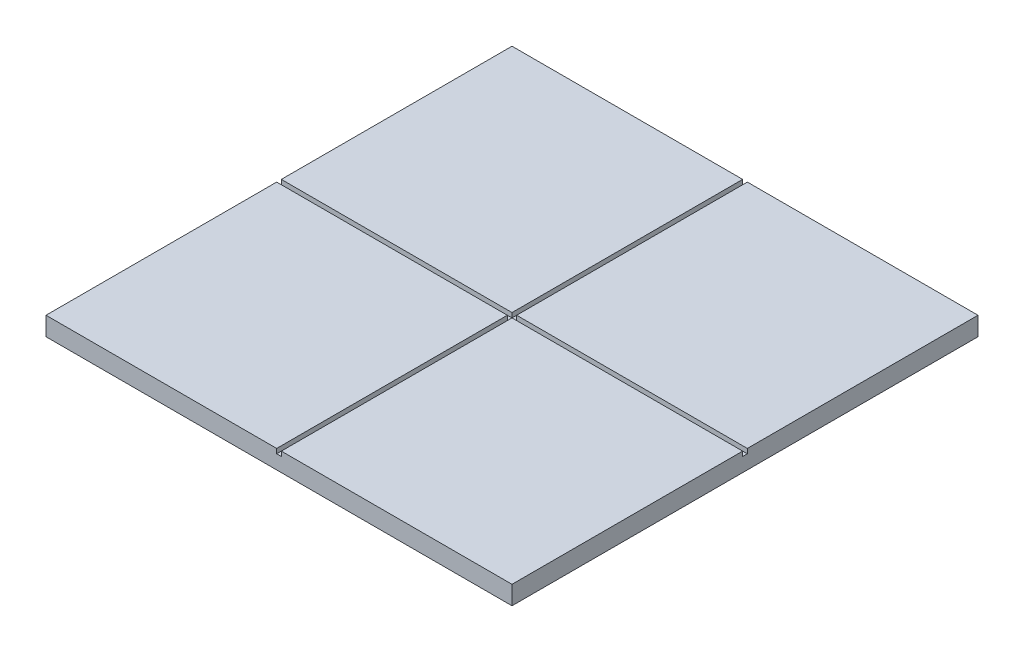
SolidWorks part; units mm, degrees
ref_plane "Front Plane" through (0, 0, 0) normal (0, 0, 1) x (1, 0, 0)
ref_plane "Top Plane" through (0, 0, 0) normal (0, 1, 0) x (1, 0, 0)
ref_plane "Right Plane" through (0, 0, 0) normal (1, 0, 0) x (0, 0, -1)
sketch "Sketch1" plane through (0, 0, 0) normal (0, 1, 0) x (1, 0, 0)
  line L1 (0, 0) -> (50, 0)
  line L2 (0, 0) -> (0, 50)
  line L3 (0, 50) -> (50, 50)
  line L4 (50, 0) -> (50, 50)
  dimension "D1" = 50
  dimension "D2" = 50
extrude "Boss-Extrude1" add sketch "Sketch1" along normal blind 2
sketch "Sketch2" plane through (0, 2, 0) normal (0, 1, 0) x (1, 0, 0)
  line L0 (50, 50) -> (0, 50) construction
  line L1 (24.75, 50) -> (25.25, 50)
  line L2 (24.75, 50) -> (24.75, 0)
  line L3 (24.75, 0) -> (25.25, 0)
  line L4 (25.25, 50) -> (25.25, 0)
  line L5 (0, 0) -> (50, 0) construction
  line L6 (0, 50) -> (0, 0) construction
  line L7 (0, 25.25) -> (50, 25.25)
  line L8 (0, 25.25) -> (0, 24.75)
  line L9 (0, 24.75) -> (50, 24.75)
  line L10 (50, 25.25) -> (50, 24.75)
  line L11 (50, 0) -> (50, 50) construction
  line M7 (0, 50) -> (0, 0)
  line M9 (50, 0) -> (50, 50)
  dimension "D1" = 0.5
  dimension "D2" = 0.5
  dimension "D3" = 24.75
  dimension "D4" = 24.75
  dimension "D5" = 24.75
  dimension "D6" = 24.75
extrude "Cut-Extrude1" cut sketch "Sketch2" against normal blind 0.5 contours L4 L9 L7 M9 | L9 L2 L7 M7 | L2 L9 L4 L7
